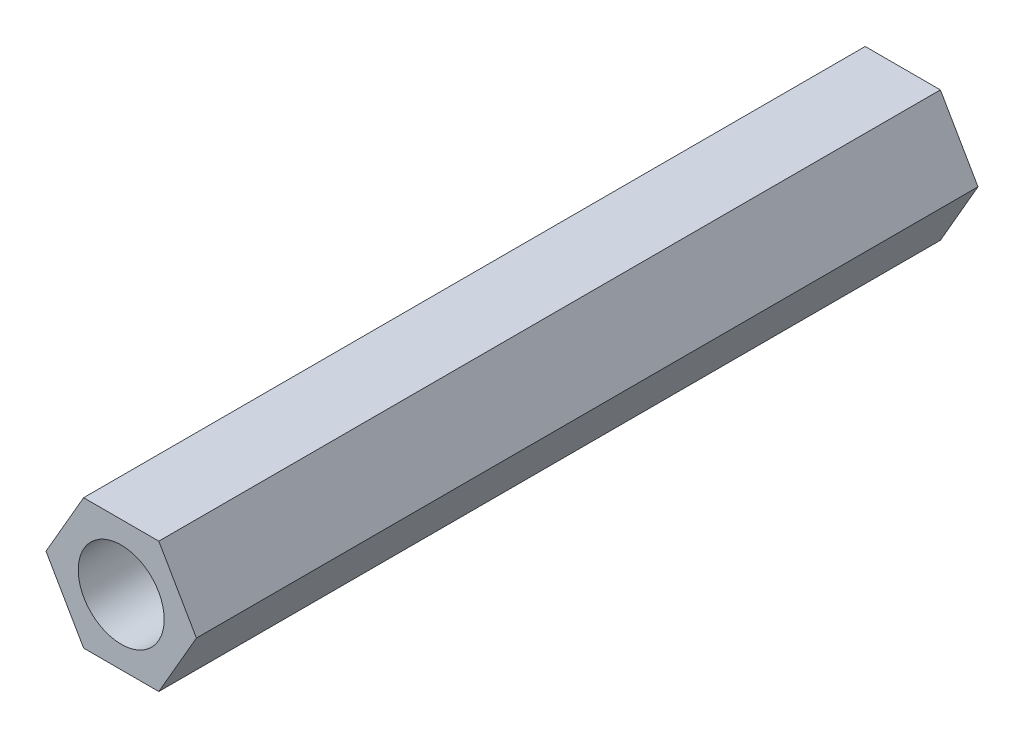
SolidWorks part; units mm, degrees
ref_plane "前视基准面" through (0, 0, 0) normal (0, 0, 1) x (1, 0, 0)
ref_plane "上视基准面" through (0, 0, 0) normal (0, 1, 0) x (1, 0, 0)
ref_plane "右视基准面" through (0, 0, 0) normal (1, 0, 0) x (0, 0, -1)
other "Configuration Table"
sketch "草图1" plane through (0, 0, 0) normal (0, 0, 1) x (1, 0, 0)
  line L0 (2.8868, 0) -> (1.4434, 2.5)
  line L1 (1.4434, 2.5) -> (-1.4434, 2.5)
  line L2 (-1.4434, 2.5) -> (-2.8868, 0)
  line L3 (-2.8868, 0) -> (-1.4434, -2.5)
  line L4 (-1.4434, -2.5) -> (1.4434, -2.5)
  line L5 (1.4434, -2.5) -> (2.8868, 0)
  circle A0 centre (0, 0) radius 1.65
extrude "30mm铝柱_M3通孔_六角5" add sketch "草图1" along normal blind 30
